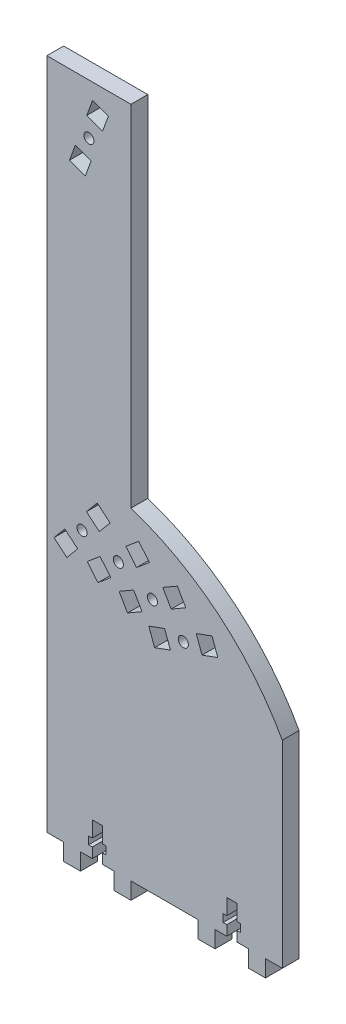
SolidWorks part; units mm, degrees
ref_plane "Plan de face" through (0, 0, 0) normal (0, 0, 1) x (1, 0, 0)
ref_plane "Plan de dessus" through (0, 0, 0) normal (0, 1, 0) x (1, 0, 0)
ref_plane "Plan de droite" through (0, 0, 0) normal (1, 0, 0) x (0, 0, -1)
sketch "Esquisse1" plane through (0, 0, 0) normal (0, 0, 1) x (1, 0, 0)
  line L0 (0, 0) -> (0, 38.8315) construction
  line L1 (-33.9845, 0) -> (30.6321, 0) construction
  line L2 (-20, 0) -> (-20, 11.2208) construction
  line L3 (-21.5, 0) -> (-25, 0)
  line L4 (-25, -5) -> (-30, -5)
  line L5 (-30, -5) -> (-30, 0)
  line L6 (-25, -5) -> (-25, 0)
  line L7 (-18.5, 0) -> (-15, 0)
  line L8 (-15, 0) -> (-15, -5)
  line L9 (-15, -5) -> (-10, -5)
  line L10 (-10, -5) -> (-10, 0)
  line L11 (-21.5, 0) -> (-18.5, 0) construction
  line L12 (-18.5, 0) -> (-18.5, 3)
  line L13 (-18.5, 5.3) -> (-17.4, 5.3)
  line L14 (-22.6, 3) -> (-22.6, 5.3)
  line L15 (-17.4, 3) -> (-18.5, 3)
  line L16 (-18.5, 5.3) -> (-18.5, 10)
  line L17 (-18.5, 10) -> (-21.5, 10)
  line L18 (-21.5, 10) -> (-21.5, 5.3)
  line L19 (-21.5, 3) -> (-22.6, 3)
  line L20 (-17.4, 5.3) -> (-17.4, 3)
  line L21 (-22.6, 5.3) -> (-21.5, 5.3)
  line L22 (-21.5, 3) -> (-21.5, 0)
  line L23 (-20, 10) -> (-20, 0) construction
  line L24 (10, -5) -> (10, 0)
  line L25 (15, -5) -> (10, -5)
  line L26 (15, 0) -> (15, -5)
  line L27 (18.5, 0) -> (15, 0)
  line L28 (18.5, 0) -> (18.5, 3)
  line L29 (17.4, 3) -> (18.5, 3)
  line L30 (17.4, 5.3) -> (17.4, 3)
  line L31 (18.5, 5.3) -> (17.4, 5.3)
  line L32 (18.5, 5.3) -> (18.5, 10)
  line L33 (18.5, 10) -> (21.5, 10)
  line L34 (21.5, 10) -> (21.5, 5.3)
  line L35 (22.6, 5.3) -> (21.5, 5.3)
  line L36 (22.6, 3) -> (22.6, 5.3)
  line L37 (21.5, 3) -> (22.6, 3)
  line L38 (21.5, 3) -> (21.5, 0)
  line L39 (21.5, 0) -> (25, 0)
  line L40 (25, -5) -> (25, 0)
  line L41 (25, -5) -> (30, -5)
  line L42 (30, -5) -> (30, 0)
  line L43 (-10, 0) -> (10, 0)
  line L44 (30, 0) -> (35, 0)
  line L45 (35, 0) -> (35, 200) construction
  line L46 (35, 200) -> (-35, 200) construction
  line L47 (-35, 200) -> (-35, 0)
  line L48 (-35, 0) -> (-30, 0)
  line L49 (35, 0) -> (35, 58.7298)
  line L52 (0, 20) -> (-35, 20) construction
  line L53 (-10, 95.9934) -> (-10, 200)
  line L54 (-10, 200) -> (-35, 200)
  line L55 (-35, 20) -> (-57.9813, 39.2836) construction
  line L56 (-57.9813, 39.2836) -> (9.2875, 119.4515) construction
  line L57 (-35, 20) -> (-54.2836, 42.9813) construction
  line L58 (-54.2836, 42.9813) -> (25.8842, 110.2501) construction
  line L59 (-35, 20) -> (-50, 45.9808) construction
  line L60 (-50, 45.9808) -> (40.631, 98.3066) construction
  line L61 (-35, 20) -> (-45.2606, 48.1908) construction
  line L62 (-45.2606, 48.1908) -> (53.0798, 83.9838) construction
  line L63 (-22.5, 200) -> (-22.5, 106.8704) construction
  arc A1 (35, 58.7298) -> (-10, 95.9934) centre (-35, 20) ccw
  point P68 (-35, 20)
  point P69 (0, 0)
  point P70 (-22.5, 177.9579)
  line B0 (-29.6722, 80.7998) -> (-32.8861, 76.9696)
  line B1 (-29.6722, 80.7998) -> (-25.842, 77.5859)
  line B2 (-25.842, 77.5859) -> (-29.0559, 73.7556)
  line B3 (-32.8861, 76.9696) -> (-29.0559, 73.7556)
  line B4 (-23.2443, 88.4602) -> (-20.0304, 92.2905)
  line B5 (-23.2443, 88.4602) -> (-19.4141, 85.2463)
  line B6 (-19.4141, 85.2463) -> (-16.2001, 89.0765)
  line B7 (-20.0304, 92.2905) -> (-16.2001, 89.0765)
  line B8 (-24.5431, 83.023) -> (-29.8843, 87.5048) construction
  circle B9 centre (-24.5431, 83.023) radius 1.5
  line B10 (-19.1953, 78.9509) -> (-23.0256, 75.737)
  line B11 (-19.1953, 78.9509) -> (-15.9814, 75.1207)
  line B12 (-15.9814, 75.1207) -> (-19.8116, 71.9068)
  line B13 (-23.0256, 75.737) -> (-19.8116, 71.9068)
  line B14 (-11.5349, 85.3788) -> (-7.7047, 88.5928)
  line B15 (-11.5349, 85.3788) -> (-8.321, 81.5486)
  line B16 (-8.321, 81.5486) -> (-4.4907, 84.7625)
  line B17 (-7.7047, 88.5928) -> (-4.4907, 84.7625)
  circle B18 centre (-13.7582, 80.2498) radius 1.5
  line B19 (-9.1987, 75.3109) -> (-13.5289, 72.8109)
  line B20 (-9.1987, 75.3109) -> (-6.6987, 70.9808)
  line B21 (-6.6987, 70.9808) -> (-11.0289, 68.4808)
  line B22 (-13.5289, 72.8109) -> (-11.0289, 68.4808)
  line B23 (-0.5385, 80.3109) -> (3.7917, 82.8109)
  line B24 (-0.5385, 80.3109) -> (1.9615, 75.9808)
  line B25 (1.9615, 75.9808) -> (6.2917, 78.4808)
  line B26 (3.7917, 82.8109) -> (6.2917, 78.4808)
  circle B27 centre (-3.6186, 75.6458) radius 1.5
  line B28 (0.0139, 69.9902) -> (-4.6845, 68.2801)
  line B29 (0.0139, 69.9902) -> (1.724, 65.2918)
  line B30 (1.724, 65.2918) -> (-2.9744, 63.5817)
  line B31 (-4.6845, 68.2801) -> (-2.9744, 63.5817)
  line B32 (9.4109, 73.4105) -> (14.1093, 75.1206)
  line B33 (9.4109, 73.4105) -> (11.121, 68.712)
  line B34 (11.121, 68.712) -> (15.8194, 70.4221)
  line B35 (14.1093, 75.1206) -> (15.8194, 70.4221)
  circle B36 centre (5.5674, 69.3511) radius 1.5
  line B37 (-24.2101, 180.3015) -> (-20.7899, 189.6985) construction
  line B38 (-26.5593, 181.1566) -> (-28.2694, 176.4581)
  line B39 (-26.5593, 181.1566) -> (-21.8609, 179.4465)
  line B40 (-21.8609, 179.4465) -> (-23.571, 174.748)
  line B41 (-28.2694, 176.4581) -> (-23.571, 174.748)
  line B42 (-23.1391, 190.5535) -> (-21.429, 195.252)
  line B43 (-23.1391, 190.5535) -> (-18.4407, 188.8434)
  line B44 (-18.4407, 188.8434) -> (-16.7306, 193.5419)
  line B45 (-21.429, 195.252) -> (-16.7306, 193.5419)
  circle B46 centre (-22.5, 185) radius 1.5
  dimension "D14" = 80
  dimension "D1" = 20
  dimension "D2" = 10
  dimension "D3" = 5
  dimension "D4" = 5
  dimension "D5" = 5.2
  dimension "D6" = 3
  dimension "D7" = 2.3
  dimension "D8" = 3
  dimension "D9" = 10
  dimension "D10" = 5
  dimension "D11" = 5
  dimension "D12" = 200
  dimension "D13" = 20
  dimension "D15" = 25
  dimension "D16" = 30
  dimension "D17" = 50
  dimension "D18" = 55
  dimension "D20" = 10
  dimension "D21" = 15
  dimension "D22" = 20
  dimension "D19" = 4
sketch_block_instance "Trou M3 plots 5mm-1"
sketch_block "Trou M3 plots 5mm" parameters "D2"=3, "D1"=5, "D3"=5, "D4"=10
sketch_block_instance "Trou M3 plots 5mm-3"
sketch_block_instance "Trou M3 plots 5mm-4"
sketch_block_instance "Trou M3 plots 5mm-5"
sketch_block_instance "Trou M3 plots 5mm-6"
extrude "Boss.-Extru.1" add sketch "Esquisse1" along normal blind 5
